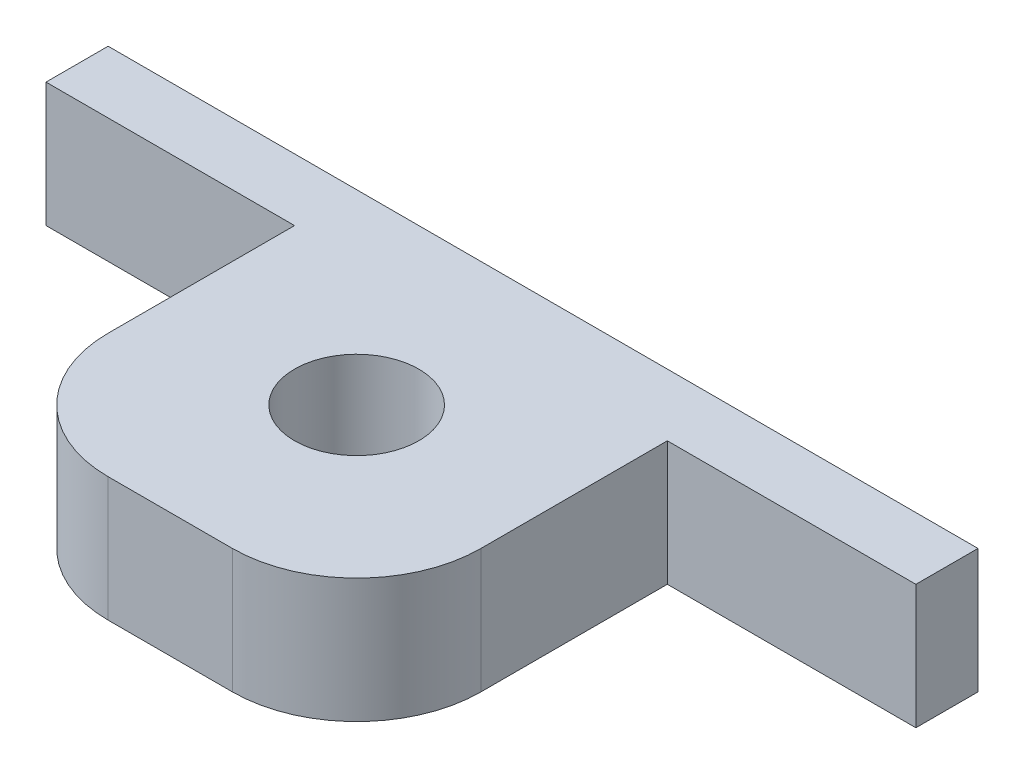
SolidWorks part; units mm, degrees
ref_plane "Front Plane" through (0, 0, 0) normal (1, 0, 0) x (0, 1, 0)
ref_plane "Top Plane" through (0, 0, 0) normal (0, 0, 1) x (0, 1, 0)
ref_plane "Right Plane" through (0, 0, 0) normal (0, 1, 0) x (-1, 0, 0)
sketch "Sketch1" plane through (0, 0, 0) normal (0, 1, 0) x (-1, 0, 0)
  line L0 (-70, 0) -> (70, 0)
  line L1 (70, 0) -> (70, 10)
  line L2 (70, 10) -> (30, 10)
  line L3 (30, 10) -> (30, 60)
  line L4 (30, 60) -> (-30, 60)
  line L5 (-30, 60) -> (-30, 10)
  line L6 (-30, 10) -> (-70, 10)
  line L7 (-70, 10) -> (-70, 0)
  circle A0 centre (0, 30) radius 10
  point P9 (0, 60)
  point P10 (0, 0)
  point P13 (0, 0)
  dimension "D5" = 20
  dimension "D1" = 10
  dimension "D2" = 60
  dimension "D3" = 40
  dimension "D4" = 60
  dimension "D6" = 30
extrude "Boss-Extrude1" add sketch "Sketch1" along normal mid plane 20
fillet "Fillet1" radius 20 2 edges at (-30, 0, 60) (30, 0, 60)
